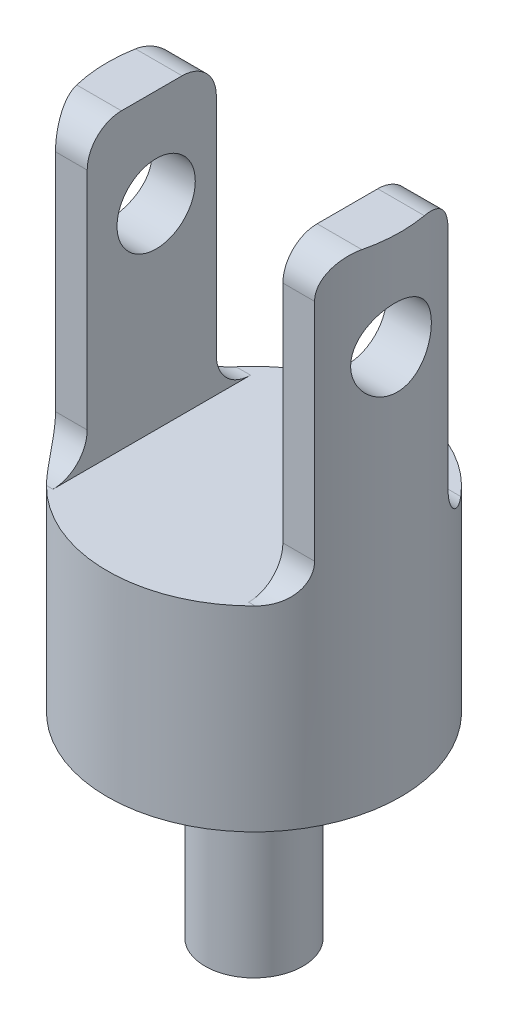
SolidWorks part; units mm, degrees
ref_plane "Front Plane" through (0, 0, 0) normal (0, 0, 1) x (1, 0, 0)
ref_plane "Top Plane" through (0, 0, 0) normal (0, 1, 0) x (1, 0, 0)
ref_plane "Right Plane" through (0, 0, 0) normal (1, 0, 0) x (0, 0, -1)
sketch "Sketch1" plane through (0, 0, 0) normal (0, 1, 0) x (1, 0, 0)
  circle A0 centre (0, 0) radius 15
extrude "Boss-Extrude1" add sketch "Sketch1" along normal blind 50
sketch "Sketch2" plane through (0, 0, 0) normal (0, -1, 0) x (1, 0, 0)
  circle A0 centre (0, 0) radius 5
extrude "Boss-Extrude2" add sketch "Sketch2" along normal blind 20
sketch "Sketch3" plane through (0, 50, 0) normal (0, 1, 0) x (1, 0, 0)
  line L1 (-10, 24.0793) -> (10, 24.0793)
  line L2 (-10, 24.0793) -> (-10, -24.0793)
  line L3 (-10, -24.0793) -> (10, -24.0793)
  line L4 (10, 24.0793) -> (10, -24.0793)
  line L5 (-10, 24.0793) -> (10, -24.0793) construction
  line L6 (-10, -24.0793) -> (10, 24.0793) construction
  point P0 (0, 0)
  dimension "D1" = 20
extrude "Cut-Extrude1" cut sketch "Sketch3" against normal blind 30
sketch "Sketch4" plane through (0, 50, 0) normal (0, 1, 0) x (1, 0, 0)
  line L0 (0, 0) -> (24.3129, -0.833) construction
  line L1 (-13.9687, 19.0961) -> (15.2139, 19.0961)
  line L2 (-13.9687, 19.0961) -> (-13.9687, 7.0481)
  line L3 (-13.9687, 7.0481) -> (15.2139, 7.0481)
  line L4 (15.2139, 19.0961) -> (15.2139, 7.0481)
  line L5 (-13.9687, 19.0961) -> (15.2139, 7.0481) construction
  line L6 (-13.9687, 7.0481) -> (15.2139, 19.0961) construction
  line L7 (24.3129, -0.833) -> (-18.637, 0.6385) construction
  point P0 (0.6226, 13.0721)
  point P8 (15.2139, 19.0961)
  point P13 (0, 0)
  point P14 (0, 0)
  point P15 (0, 0)
  line M7 (10, 11.1803) -> (10, -11.1803)
  arc M8 (10, -11.1803) -> (10, 11.1803) centre (0, 0) ccw
extrude "Cut-Extrude4" cut sketch "Sketch4" against normal blind 30 contours L4 L1 L2 L3 M7 M8 | L3 M7 M8
sketch "Sketch7" plane through (0, 50, 0) normal (0, 1, 0) x (1, 0, 0)
  line L1 (37.9211, 6.15) -> (-27.657, 6.15)
  line L2 (37.9211, 6.15) -> (37.9211, 29.1236)
  line L3 (37.9211, 29.1236) -> (-27.657, 29.1236)
  line L4 (-27.657, 6.15) -> (-27.657, 29.1236)
  line L5 (37.9211, 6.15) -> (-27.657, 29.1236) construction
  line L6 (37.9211, 29.1236) -> (-27.657, 6.15) construction
  point P0 (5.132, 17.6368)
extrude "Cut-Extrude5" cut sketch "Sketch7" against normal blind 30
mirror "Mirror1" about plane through (0, 0, 0) normal (0, 0, 1) of "Cut-Extrude4"
fillet "Fillet6" radius 3.5 8 edges at (-11.8406, 50, -6.15) (-11.8406, 20, -6.15) (11.8406, 20, -6.15) (11.8406, 50, -6.15) (11.6205, 50, 7.0481) (11.6205, 20, 7.0481) (-11.6205, 20, 7.0481) (-11.6205, 50, 7.0481)
sketch "Sketch9" plane through (-10, 0, 0) normal (1, 0, 0) x (0, 0, -1)
  line L0 (0, 50) -> (0, 40) construction
  line L1 (2.65, 50) -> (-3.5481, 50) construction
  circle A0 centre (0, 40) radius 4
  dimension "D1" = 10
extrude "Cut-Extrude6" cut sketch "Sketch9" against normal through all
sketch "Sketch11" plane through (10, 0, 0) normal (-1, 0, 0) x (0, 0, 1)
  line L0 (0.4491, 50) -> (0.4491, 40) construction
  line L1 (3.5481, 50) -> (-2.65, 50) construction
  circle A0 centre (0.4491, 40) radius 4
  dimension "D1" = 10
extrude "Cut-Extrude7" cut sketch "Sketch11" against normal through all contours A0
